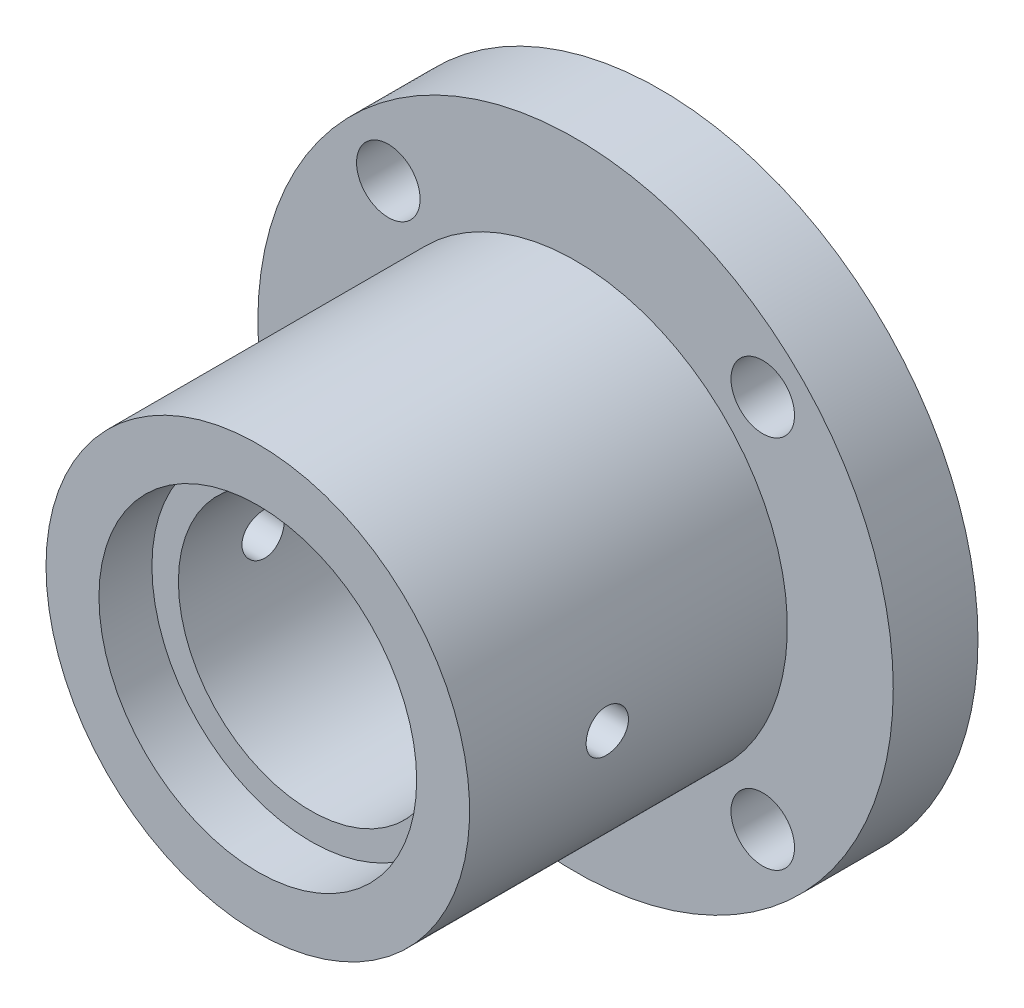
SolidWorks part; units mm, degrees
ref_plane "前视基准面" through (0, 0, 0) normal (0, 0, 1) x (1, 0, 0)
ref_plane "上视基准面" through (0, 0, 0) normal (0, 1, 0) x (1, 0, 0)
ref_plane "右视基准面" through (0, 0, 0) normal (1, 0, 0) x (0, 0, -1)
sketch "草图1" plane through (0, 0, 0) normal (0, 1, 0) x (1, 0, 0)
  line L0 (0, 0) -> (0, -38) construction
  line L1 (0, 0) -> (30, 0)
  line L2 (30, 0) -> (30, -8)
  line L3 (30, -8) -> (20, -8)
  line L4 (20, -8) -> (20, -38)
  line L5 (20, -38) -> (0, -38)
  line L6 (0, -38) -> (0, 0)
revolve "旋转1" add sketch "草图1" angle 360 about L0
ref_plane "基准面1" through (0, 0, 38) normal (0, 0, 1) x (1, 0, 0)
sketch "草图2" plane through (0, 0, 38) normal (0, 0, 1) x (1, 0, 0)
  circle A0 centre (0, 0) radius 15
extrude "切除-拉伸1" cut sketch "草图2" against normal blind 5
sketch "草图3" plane through (0, 0, 38) normal (0, 0, 1) x (1, 0, 0)
  circle A0 centre (0, 0) radius 12.5
extrude "切除-拉伸2" cut sketch "草图3" against normal through all
sketch "草图5" plane through (0, 0, 0) normal (0, 0, 1) x (1, 0, 0)
  circle A0 centre (17.6777, 17.6777) radius 3
  circle A1 centre (-17.6777, 17.6777) radius 3
  circle A2 centre (-17.6777, -17.6777) radius 3
  circle A3 centre (17.6777, -17.6777) radius 3
extrude "切除-拉伸5" cut sketch "草图5" along normal through all
sketch "草图6" plane through (0, 0, 0) normal (1, 0, 0) x (0, 0, -1)
  circle A0 centre (-25, 0) radius 2
extrude "切除-拉伸6" cut sketch "草图6" against normal mid plane 122
